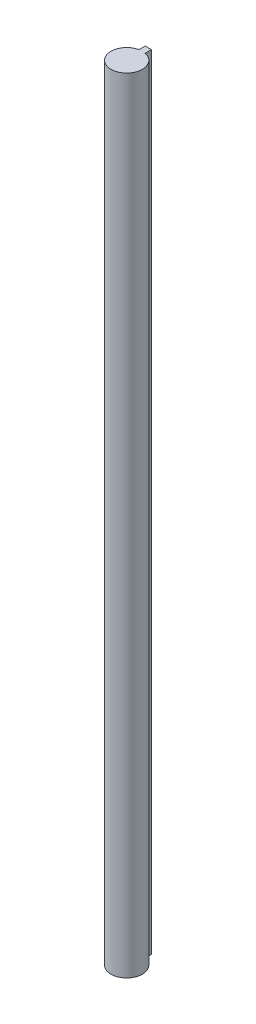
SolidWorks part; units mm, degrees
ref_plane "前视基准面" through (0, 0, 0) normal (0, 0, 1) x (1, 0, 0)
ref_plane "上视基准面" through (0, 0, 0) normal (0, 1, 0) x (1, 0, 0)
ref_plane "右视基准面" through (0, 0, 0) normal (1, 0, 0) x (0, 0, -1)
sketch "草图1" plane through (0, 0, 0) normal (0, 1, 0) x (1, 0, 0)
  line L1 (0, -6.6512) -> (0, 18.474) construction
  line L2 (-2, 9.798) -> (-2, 13.798)
  line L3 (-2, 13.798) -> (2, 13.798)
  line L4 (2, 9.798) -> (2, 13.798)
  arc A0 (-2, 9.798) -> (2, 9.798) centre (0, 0) ccw
  point P10 (0, 13.798)
  dimension "D1" = 4
  dimension "D3" = 10
  dimension "D2" = 4
extrude "凸台-拉伸1" add sketch "草图1" along normal blind 500
